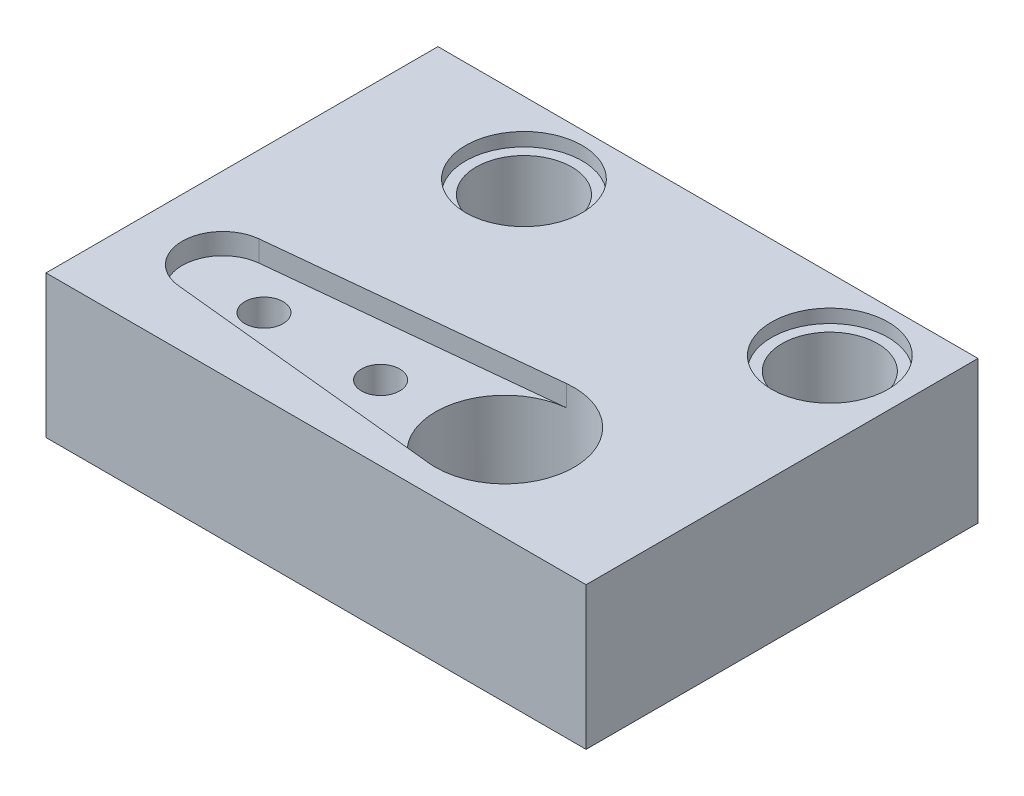
SolidWorks part; units mm, degrees
ref_plane "Front Plane" through (0, 0, 0) normal (0, 0, 1) x (1, 0, 0)
ref_plane "Top Plane" through (0, 0, 0) normal (0, 1, 0) x (1, 0, 0)
ref_plane "Right Plane" through (0, 0, 0) normal (1, 0, 0) x (0, 0, -1)
sketch "Sketch1" plane through (0, 0, 0) normal (0, 1, 0) x (1, 0, 0)
  line L0 (0, 12.1071) -> (0, -10.3651) construction
  line L1 (-19.1976, 0) -> (16.8443, 0) construction
  line L2 (-14.75, 6.703) -> (-14.75, -5.4465) construction
  line L3 (9.25, 15.5) -> (-19, 15.5)
  line L4 (-19, 15.5) -> (-19, -5)
  line L5 (9.25, 15.5) -> (9.25, -5)
  line L6 (-19, 11.75) -> (9.25, 11.75) construction
  line L7 (-4.875, 15.5) -> (-4.875, -5.7439) construction
  line L8 (0, 3.6062) -> (9.25, 3.6062) construction
  line L9 (-14.9661, 2.114) -> (-0.3686, 3.6062) construction
  line L10 (9.25, -4.25) -> (-19, -4.25) construction
  line L11 (-19, -5) -> (9.25, -5)
  circle A0 centre (0, 0) radius 3.625 construction
  circle A1 centre (-14.75, 0) radius 2.125 construction
  circle A2 centre (5.25, 11.75) radius 2.5
  circle A3 centre (-10.75, 11.75) radius 2.5
  point P28 (9.25, 0)
  point P29 (-19, 0)
  dimension "D2" = 7.25
  dimension "D3" = 4.25
  dimension "D7" = 3.75
  dimension "D8" = 5
  dimension "D10" = 5
  dimension "D1" = 14.75
  dimension "D4" = 9.25
  dimension "D5" = 4.25
  dimension "D6" = 15.5
  dimension "D9" = 4
  dimension "D11" = 16
  dimension "D12" = 16
  dimension "D13" = 5
extrude "Boss-Extrude1" add sketch "Sketch1" along normal blind 7.46
sketch "Sketch3" plane through (0, 7.46, 0) normal (0, 1, 0) x (1, 0, 0)
  line L0 (9.25, 0) -> (-19, 0) construction
  line L1 (9.25, -5) -> (9.25, 15.5) construction
  line L2 (-19, 15.5) -> (-19, -5) construction
  line L3 (-19, -5) -> (9.25, -5) construction
  line L4 (-4.875, 15.5) -> (-4.875, -5) construction
  line L5 (9.25, 15.5) -> (-19, 15.5) construction
  line L6 (0, 15.5) -> (0, -5) construction
  line L7 (-14.75, 15.5) -> (-14.75, -5) construction
  line L8 (-14.9655, 2.114) -> (-0.3671, 3.6019)
  line L9 (-14.9655, -2.114) -> (-0.3671, -3.6019)
  arc A0 (-0.3671, -3.6019) -> (-0.3671, 3.6019) centre (0, 0) ccw
  arc A1 (-14.9655, 2.114) -> (-14.9655, -2.114) centre (-14.75, 0) ccw
  dimension "D4" = 4.25
  dimension "D5" = 7.2411
  dimension "D1" = 5
  dimension "D2" = 9.25
  dimension "D3" = 14.75
extrude "Cut-Extrude2" cut sketch "Sketch3" against normal blind 1.1
sketch "Sketch5" plane through (0, 6.36, 0) normal (0, 1, 0) x (1, 0, 0)
  line L0 (0, 3.6205) -> (0, -3.6205) construction
  line L1 (3.6205, 0) -> (-16.875, 0) construction
  line L2 (-6.5, 2.7009) -> (-6.5, -2.6251) construction
  line L3 (-12.6, 1.7656) -> (-12.6, -1.377) construction
  arc A0 (-0.3671, -3.6019) -> (-0.3671, 3.6019) centre (0, 0) ccw construction
  arc A1 (-14.9655, 2.114) -> (-14.9655, -2.114) centre (-14.75, 0) ccw construction
  circle A2 centre (-12.6, 0) radius 1
  circle A3 centre (-6.5, 0) radius 1
  circle A4 centre (0, 0) radius 3.6205
  dimension "D3" = 2
  dimension "D4" = 2
  dimension "D1" = 6.5
  dimension "D2" = 12.6
extrude "Cut-Extrude3" cut sketch "Sketch5" against normal through all
sketch "Sketch6" plane through (0, 7.46, 0) normal (0, 1, 0) x (1, 0, 0)
  circle A0 centre (-10.75, 11.75) radius 3.05
  circle A1 centre (5.25, 11.75) radius 3.05
  dimension "D1" = 6.1
  dimension "D2" = 6.1
extrude "Cut-Extrude4" cut sketch "Sketch6" against normal blind 0.7
sketch "Sketch7" plane through (0, 0, 0) normal (0, -1, 0) x (1, 0, 0)
  circle A0 centre (5.25, -11.75) radius 3.05
  circle A1 centre (-10.75, -11.75) radius 3.05
  dimension "D1" = 6.1
  dimension "D2" = 6.1
extrude "Cut-Extrude5" cut sketch "Sketch7" against normal blind 0.7
sketch "Sketch4" plane through (0, 7.46, 0) normal (0, 1, 0) x (1, 0, 0)
  line L0 (0, 9.25) -> (0, -5) construction
  line L1 (9.25, 9.25) -> (-19, 9.25) construction
  line L2 (-19, -5) -> (9.25, -5) construction
  line L3 (9.25, -5) -> (9.25, 9.25) construction
  line L4 (-14.25, 9.25) -> (-14.25, -5) construction
  dimension "D1" = 9.25
  dimension "D2" = 14.25
